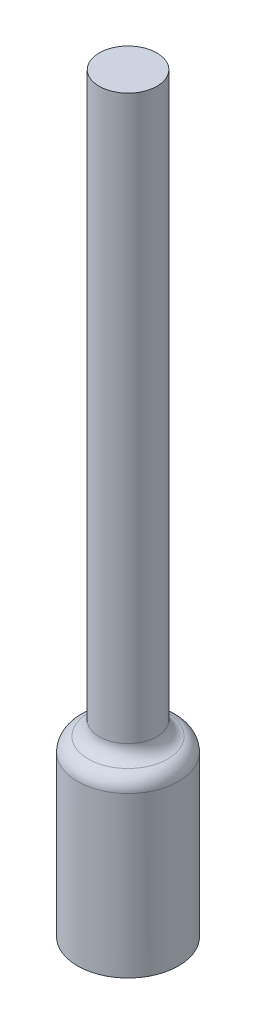
SolidWorks part; units mm, degrees
ref_plane "Спереди" through (0, 0, 0) normal (0, 0, 1) x (1, 0, 0)
ref_plane "Сверху" through (0, 0, 0) normal (0, 1, 0) x (1, 0, 0)
ref_plane "Справа" through (0, 0, 0) normal (1, 0, 0) x (0, 0, -1)
sketch "Эскиз1" plane through (0, 0, 0) normal (0, 1, 0) x (1, 0, 0)
  circle A0 centre (0, 0) radius 1.99
  circle A1 centre (0, 0) radius 3.5
  dimension "D1" = 3.98
  dimension "D2" = 7
extrude "Вытянуть1" add sketch "Эскиз1" along normal blind 12
sketch "Эскиз2" plane through (0, 12, 0) normal (0, 1, 0) x (1, 0, 0)
  circle A0 centre (0, 0) radius 2
extrude "Вытянуть2" add sketch "Эскиз2" along normal blind 40
fillet "Скругление1" radius 1 1 edges at (0, 12, 2)
fillet "Скругление2" radius 1 1 edges at (0, 12, 3.5)
sketch "Эскиз3" [suppressed] plane through (0, 0, 0) normal (1, 0, 0) x (0, 0, -1)
  line L0 (0, 52) -> (0, 54.1276) construction
